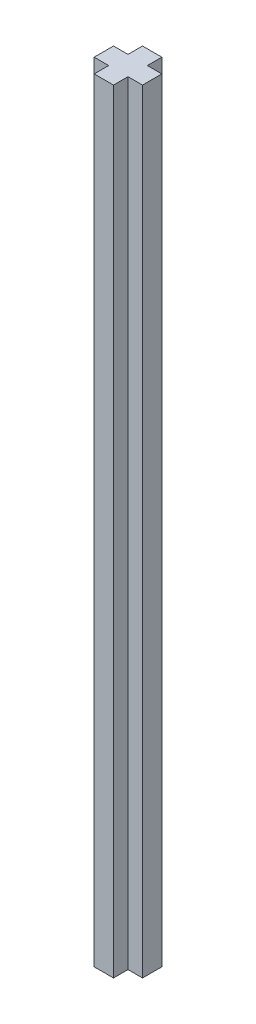
SolidWorks part; units mm, degrees
ref_plane "前视基准面" through (0, 0, 0) normal (0, 0, 1) x (1, 0, 0)
ref_plane "上视基准面" through (0, 0, 0) normal (0, 1, 0) x (1, 0, 0)
ref_plane "右视基准面" through (0, 0, 0) normal (1, 0, 0) x (0, 0, -1)
sketch "草图1" plane through (0, 0, 0) normal (0, 1, 0) x (1, 0, 0)
  line L0 (1, 1) -> (2.5, 1)
  line L1 (-1, 2.5) -> (1, 2.5)
  line L2 (-1, 2.5) -> (-1, 1)
  line L3 (-1, -2.5) -> (1, -2.5)
  line L4 (1, 2.5) -> (1, 1)
  line L7 (-2.5, 1) -> (-1, 1)
  line L8 (-2.5, 1) -> (-2.5, -1)
  line L9 (-2.5, -1) -> (-1, -1)
  line L10 (2.5, 1) -> (2.5, -1)
  line L15 (-1, -1) -> (-1, -2.5)
  line L17 (1, -1) -> (2.5, -1)
  line L19 (1, -1) -> (1, -2.5)
  point P0 (0, 0)
  point P6 (0, 0)
  dimension "D1" = 2
  dimension "D2" = 2
  dimension "D3" = 5
  dimension "D4" = 5
extrude "凸台-拉伸1" add sketch "草图1" along normal blind 80
